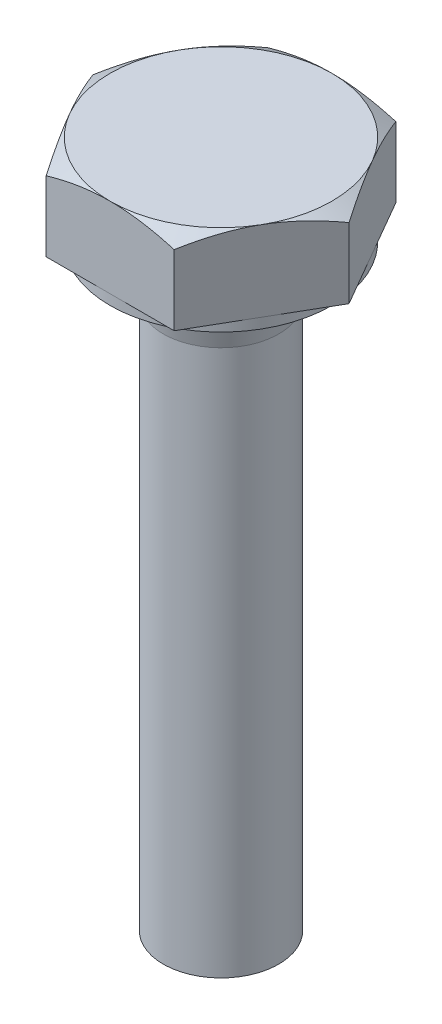
SolidWorks part; units mm, degrees
ref_plane "Vorderseite" through (0, 0, 0) normal (0, 0, 1) x (1, 0, 0)
ref_plane "Oben" through (0, 0, 0) normal (0, 1, 0) x (1, 0, 0)
ref_plane "Rechts" through (0, 0, 0) normal (1, 0, 0) x (0, 0, -1)
sketch "Skizze1" plane through (0, 0, 0) normal (0, 0, 1) x (1, 0, 0)
  line L0 (0, 5.3) -> (0, -35)
  line L1 (0, 5.3) -> (6.5, 5.3)
  line L2 (6.5, 5.3) -> (7.5055, 4.7195)
  line L3 (7.5055, 4.7195) -> (7.5055, 0.6)
  line L4 (7.5055, 0.6) -> (6.5, 0.6)
  line L5 (6.5, 0.6) -> (6.5, 0)
  line L6 (6.5, 0) -> (4, 0)
  line L7 (4, 0) -> (4, -0.002)
  line L8 (3.998, -0.002) -> (3.3865, -3)
  line L9 (3.3865, -3) -> (3.3865, -35)
  line L10 (3.3865, -35) -> (0, -35)
  line L11 (0, 5.3) -> (0, -35) construction
  line L12 (4, -0.002) -> (3.998, -0.002)
  dimension "D1" = 0.002
  dimension "D2" = 0.002
  dimension "C" = 0.6
  dimension "K" = 5.3
  dimension "D3" = 30
  dimension "E" = 15.011
  dimension "DK" = 6.773
  dimension "DG" = 8
  dimension "A" = 3
  dimension "L" = 35
revolve "Basis-Rotation" add sketch "Skizze1" angle 360 about L11
sketch "Skizze2" plane through (0, 5.3, 0) normal (0, 1, 0) x (-1, 0, 0)
  line L0 (-7.5056, 0) -> (7.5056, 0) construction
  line L1 (0, 6.5) -> (0, -6.5) construction
  line L2 (-3.7528, 6.5) -> (3.7528, 6.5)
  line L3 (3.7528, 6.5) -> (7.5056, 0)
  line L4 (-3.7528, 6.5) -> (-7.5056, 0)
  line L5 (-3.7528, -6.5) -> (-7.5056, 0)
  line L6 (3.7528, -6.5) -> (7.5056, 0)
  line L7 (-3.7528, -6.5) -> (3.7528, -6.5)
  point P10 (0, 6.5)
  point P12 (0, -6.5)
  dimension "D1" = 120
extrude "Schnitt-Linear austragen1" cut sketch "Skizze2" against normal through all flip side to cut
